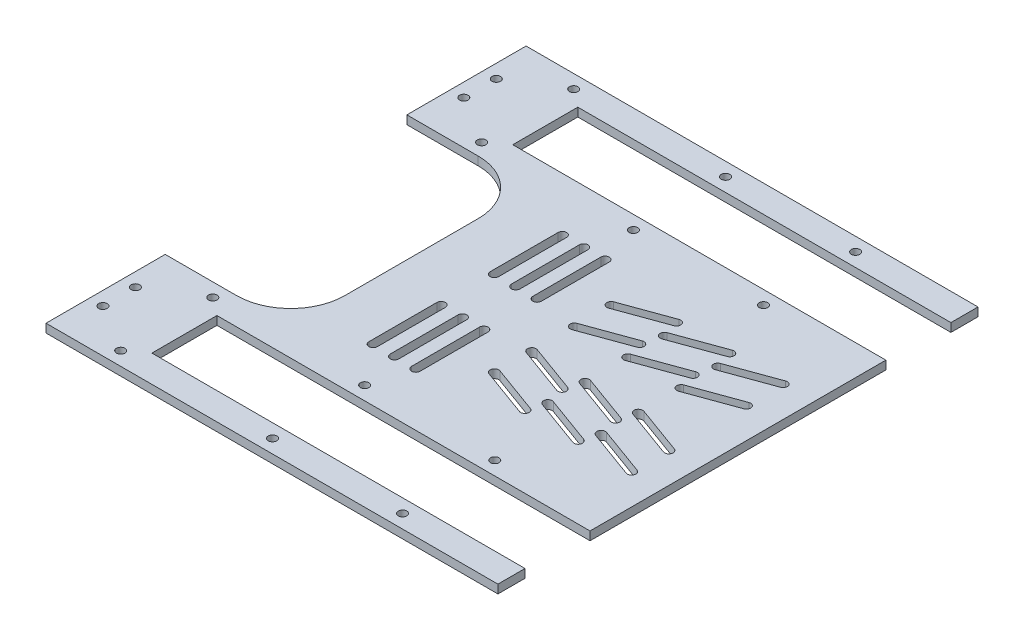
SolidWorks part; units mm, degrees
ref_plane "Front Plane" through (0, 0, 0) normal (0, 0, 1) x (1, 0, 0)
ref_plane "Top Plane" through (0, 0, 0) normal (0, 1, 0) x (1, 0, 0)
ref_plane "Right Plane" through (0, 0, 0) normal (1, 0, 0) x (0, 0, -1)
sketch "Sketch1" plane through (0, 0, 0) normal (0, 1, 0) x (1, 0, 0)
  line L0 (-55.952, 28.5339) -> (-55.9511, 28.5339)
  line L1 (-55.9511, 28.5339) -> (-55.9511, 28.321)
  line L2 (-55.9511, 28.321) -> (-21.4553, 28.321)
  line L3 (-21.4553, 28.321) -> (-21.4553, -28.321)
  line L4 (-21.4553, -28.321) -> (-55.952, -28.321)
  line L5 (-55.952, -28.321) -> (-55.952, -63.881)
  line L6 (-55.952, -63.881) -> (55.046, -63.881)
  line L7 (55.046, -63.881) -> (55.046, -57.531)
  line L8 (55.046, -57.531) -> (32.4585, -57.531)
  line L10 (32.4585, -34.671) -> (55.046, -34.671)
  line L11 (55.046, -34.671) -> (55.046, 34.671)
  line L12 (55.046, 34.671) -> (32.4585, 34.671)
  line L14 (32.4585, 57.531) -> (55.046, 57.531)
  line L15 (55.046, 57.531) -> (55.046, 63.881)
  line L16 (55.046, 63.881) -> (-55.952, 63.881)
  line L17 (-55.952, 63.881) -> (-55.952, 28.5339)
  line L18 (-21.4553, 0) -> (55.046, 0) construction
  line L19 (-55.952, -46.101) -> (-28.5899, -46.101) construction
  line L20 (32.4585, -34.671) -> (-28.5899, -34.671)
  line L21 (-28.5899, -34.671) -> (-28.5899, -46.101)
  line L22 (-28.5899, -46.101) -> (-28.5899, -57.531)
  line L23 (-28.5899, -57.531) -> (32.4585, -57.531)
  line L24 (-28.5899, 57.531) -> (32.4585, 57.531)
  line L25 (-28.5899, 46.101) -> (-28.5899, 57.531)
  line L26 (-28.5899, 34.671) -> (-28.5899, 46.101)
  line L27 (32.4585, 34.671) -> (-28.5899, 34.671)
  dimension "D1" = 28.321
  dimension "D2" = 27.3621
extrude "Boss-Extrude1" add sketch "Sketch1" along normal blind 2
fillet "Fillet1" radius 12.7 2 edges at (-21.4553, 1, 28.321) (-21.4553, 1, -28.321)
sketch "Sketch2" plane through (0, 2, 0) normal (0, 1, 0) x (1, 0, 0)
  line L36 (0, 0) -> (55.046, 0) construction
  line L37 (55.046, -34.671) -> (55.046, 34.671) construction
  circle A0 centre (51.871, 0) radius 1
  circle A1 centre (51.871, 14.1605) radius 1
  circle A2 centre (-18.2803, 0) radius 1
  circle A3 centre (-18.2803, -14.1605) radius 1
  circle A4 centre (-18.2803, 14.1605) radius 1
  circle A5 centre (-36.539, 31.496) radius 1
  circle A6 centre (-0.9481, 31.496) radius 1
  circle A7 centre (29.5319, 31.4883) radius 1
  circle A8 centre (-52.777, 45.1485) radius 1
  circle A9 centre (-52.777, 53.4035) radius 1
  circle A10 centre (-36.539, 60.706) radius 1
  circle A11 centre (-0.9481, 60.706) radius 1
  circle A12 centre (29.5319, 60.7137) radius 1
  circle A13 centre (29.5319, -60.7137) radius 1
  circle A14 centre (-0.9481, -60.706) radius 1
  circle A15 centre (-36.539, -60.706) radius 1
  circle A16 centre (-52.777, -53.4035) radius 1
  circle A17 centre (-52.777, -45.1485) radius 1
  circle A18 centre (29.5319, -31.4883) radius 1
  circle A19 centre (-0.9481, -31.496) radius 1
  circle A20 centre (-36.539, -31.496) radius 1
  circle A21 centre (51.871, -14.1605) radius 1
  dimension "D1" = 2
extrude "Cut-Extrude1" cut sketch "Sketch2" against normal through all both and the other way through all
sketch "Sketch3" plane through (0, 2, 0) normal (0, 1, 0) x (1, 0, 0)
  line L0 (-28.5899, -57.531) -> (-32.3999, -57.531)
  line L1 (-32.3999, -57.531) -> (-32.3999, -34.671)
  line L2 (-32.3999, -34.671) -> (-28.5899, -34.671)
  line L3 (-28.5899, -34.671) -> (-28.5899, -57.531)
  line L4 (-21.4553, 0) -> (55.046, 0) construction
  line L5 (-21.4553, 15.621) -> (-21.4553, -15.621) construction
  line L6 (55.046, -34.671) -> (55.046, 34.671) construction
  line L7 (-28.5899, 34.671) -> (-28.5899, 57.531)
  line L8 (-32.3999, 34.671) -> (-28.5899, 34.671)
  line L9 (-32.3999, 57.531) -> (-32.3999, 34.671)
  line L10 (-28.5899, 57.531) -> (-32.3999, 57.531)
  dimension "D1" = 3.81
extrude "Cut-Extrude2" cut sketch "Sketch3" against normal through all both and the other way through all
sketch "Sketch5" plane through (0, 2, 0) normal (0, 1, 0) x (1, 0, 0)
  line L0 (-18.2803, 0) -> (-8.2803, 0) construction
  line L1 (-8.2803, -34.671) -> (-8.2803, 34.671) construction
  line L2 (55.046, 34.671) -> (-32.3999, 34.671) construction
  line L3 (-8.2803, 34.671) -> (-8.2803, 22.171) construction
  line L4 (-8.2803, -34.671) -> (-8.2803, -22.171) construction
  line L5 (-8.2803, -6.25) -> (-8.2803, 6.25) construction
  line L6 (-8.2803, 22.171) -> (-8.2803, 6.25) construction
  line L7 (-7.2803, 22.171) -> (-7.2803, 6.25)
  line L8 (-9.2803, 22.171) -> (-9.2803, 6.25)
  line L9 (-8.2803, -22.171) -> (-8.2803, -6.25) construction
  line L10 (-7.2803, -22.171) -> (-7.2803, -6.25)
  line L11 (-9.2803, -22.171) -> (-9.2803, -6.25)
  line L12 (-7.2803, 14.2105) -> (-4.2803, 14.2105) construction
  line L13 (-5.7803, 14.2105) -> (-5.7803, 6.25) construction
  line L14 (-3.2803, 22.171) -> (-3.2803, 6.25) construction
  line L15 (-4.2803, 22.171) -> (-4.2803, 6.25)
  line L16 (-2.2803, 22.171) -> (-2.2803, 6.25)
  line L17 (-2.2803, 14.2105) -> (0.7197, 14.2105) construction
  line L18 (-0.7803, 14.2105) -> (-0.7803, 6.25) construction
  line L19 (1.7197, 22.171) -> (1.7197, 6.25) construction
  line L20 (2.7197, 22.171) -> (2.7197, 6.25)
  line L21 (0.7197, 22.171) -> (0.7197, 6.25)
  line L22 (1.7197, -22.171) -> (1.7197, -6.25) construction
  line L23 (2.7197, -22.171) -> (2.7197, -6.25)
  line L24 (0.7197, -22.171) -> (0.7197, -6.25)
  line L25 (-3.2803, -22.171) -> (-3.2803, -6.25) construction
  line L26 (-4.2803, -22.171) -> (-4.2803, -6.25)
  line L27 (-2.2803, -22.171) -> (-2.2803, -6.25)
  arc A0 (-7.2803, 22.171) -> (-9.2803, 22.171) centre (-8.2803, 22.171) ccw
  arc A1 (-9.2803, 6.25) -> (-7.2803, 6.25) centre (-8.2803, 6.25) ccw
  arc A2 (-7.2803, -22.171) -> (-9.2803, -22.171) centre (-8.2803, -22.171) cw
  arc A3 (-9.2803, -6.25) -> (-7.2803, -6.25) centre (-8.2803, -6.25) cw
  arc A4 (-4.2803, 22.171) -> (-2.2803, 22.171) centre (-3.2803, 22.171) cw
  arc A5 (-2.2803, 6.25) -> (-4.2803, 6.25) centre (-3.2803, 6.25) cw
  arc A6 (2.7197, 22.171) -> (0.7197, 22.171) centre (1.7197, 22.171) ccw
  arc A7 (0.7197, 6.25) -> (2.7197, 6.25) centre (1.7197, 6.25) ccw
  arc A8 (2.7197, -22.171) -> (0.7197, -22.171) centre (1.7197, -22.171) cw
  arc A9 (0.7197, -6.25) -> (2.7197, -6.25) centre (1.7197, -6.25) cw
  arc A10 (-4.2803, -22.171) -> (-2.2803, -22.171) centre (-3.2803, -22.171) ccw
  arc A11 (-2.2803, -6.25) -> (-4.2803, -6.25) centre (-3.2803, -6.25) ccw
  point P8 (-8.2803, 0)
  point P13 (-8.2803, 0)
  point P14 (-8.2803, 14.2105)
  point P19 (-8.2803, -14.2105)
  point P30 (-3.2803, 14.2105)
  point P41 (1.7197, 14.2105)
  point P48 (1.7197, -14.2105)
  point P55 (-3.2803, -14.2105)
  dimension "D1" = 10
  dimension "D2" = 3
  dimension "D3" = 12.5
  dimension "D4" = 12.5
  dimension "D5" = 2
  dimension "D6" = 3
extrude "Cut-Extrude3" cut sketch "Sketch5" against normal through all
sketch "Sketch6" plane through (0, 2, 0) normal (0, 1, 0) x (1, 0, 0)
  line L0 (2.7197, 14.2105) -> (8.7197, 14.2105) construction
  line L1 (2.7197, 6.25) -> (2.7197, 22.171) construction
  line L2 (0, 0) -> (8.7197, 0) construction
  line L3 (8.7197, -5) -> (8.7197, 5)
  line L4 (8.7197, 5) -> (11.7197, 5) construction
  line L5 (11.7197, 5) -> (26.6806, 10.4453) construction
  line L6 (-9.2803, 22.171) -> (-9.2803, 6.25) construction
  line L7 (19.2001, 7.7227) -> (26.6806, 10.4453) construction
  line L10 (22.9403, 9.084) -> (11.7197, 5)
  line L11 (22.9403, 9.084) -> (11.7197, 5) construction
  line L12 (23.2824, 8.1443) -> (12.0617, 4.0603)
  line L13 (22.5983, 10.0237) -> (11.3777, 5.9397)
  line L14 (35.4403, 9.084) -> (24.2197, 5) construction
  line L15 (35.7824, 8.1443) -> (24.5617, 4.0603)
  line L16 (35.0983, 10.0237) -> (23.8777, 5.9397)
  line L17 (47.9403, 9.084) -> (36.7197, 5) construction
  line L18 (48.2824, 8.1443) -> (37.0617, 4.0603)
  line L19 (47.5983, 10.0237) -> (36.3777, 5.9397)
  line L20 (22.9403, 9.084) -> (35.4403, 9.084) construction
  line L21 (17.33, 7.042) -> (17.33, 15.542) construction
  line L22 (22.8709, 17.7515) -> (11.6503, 13.6675) construction
  line L23 (23.2129, 16.8118) -> (11.9923, 12.7279)
  line L24 (22.5289, 18.6912) -> (11.3083, 14.6072)
  line L25 (35.3709, 17.7515) -> (24.1503, 13.6675) construction
  line L26 (35.7129, 16.8118) -> (24.4923, 12.7279)
  line L27 (35.0289, 18.6912) -> (23.8083, 14.6072)
  line L28 (47.8709, 17.7515) -> (36.6503, 13.6675) construction
  line L29 (48.2129, 16.8118) -> (36.9923, 12.7279)
  line L30 (47.5289, 18.6912) -> (36.3083, 14.6072)
  line L31 (22.8709, 17.7515) -> (35.3709, 17.7515) construction
  line L32 (8.7197, 0) -> (51.871, 0) construction
  line L33 (47.9403, -9.084) -> (36.7197, -5) construction
  line L34 (48.2824, -8.1443) -> (37.0617, -4.0603)
  line L35 (47.5983, -10.0237) -> (36.3777, -5.9397)
  line L36 (35.4403, -9.084) -> (24.2197, -5) construction
  line L37 (35.7824, -8.1443) -> (24.5617, -4.0603)
  line L38 (35.0983, -10.0237) -> (23.8777, -5.9397)
  line L39 (22.9403, -9.084) -> (11.7197, -5) construction
  line L40 (23.2824, -8.1443) -> (12.0617, -4.0603)
  line L41 (22.5983, -10.0237) -> (11.3777, -5.9397)
  line L42 (47.8709, -17.7515) -> (36.6503, -13.6675) construction
  line L43 (48.2129, -16.8118) -> (36.9923, -12.7279)
  line L44 (47.5289, -18.6912) -> (36.3083, -14.6072)
  line L45 (35.3709, -17.7515) -> (24.1503, -13.6675) construction
  line L46 (35.7129, -16.8118) -> (24.4923, -12.7279)
  line L47 (35.0289, -18.6912) -> (23.8083, -14.6072)
  line L48 (22.8709, -17.7515) -> (11.6503, -13.6675) construction
  line L49 (23.2129, -16.8118) -> (11.9923, -12.7279)
  line L50 (22.5289, -18.6912) -> (11.3083, -14.6072)
  arc A0 (23.2824, 8.1443) -> (22.5983, 10.0237) centre (22.9403, 9.084) ccw
  arc A1 (11.3777, 5.9397) -> (12.0617, 4.0603) centre (11.7197, 5) ccw
  arc A2 (35.7824, 8.1443) -> (35.0983, 10.0237) centre (35.4403, 9.084) ccw
  arc A3 (23.8777, 5.9397) -> (24.5617, 4.0603) centre (24.2197, 5) ccw
  arc A4 (48.2824, 8.1443) -> (47.5983, 10.0237) centre (47.9403, 9.084) ccw
  arc A5 (36.3777, 5.9397) -> (37.0617, 4.0603) centre (36.7197, 5) ccw
  arc A6 (23.2129, 16.8118) -> (22.5289, 18.6912) centre (22.8709, 17.7515) ccw
  arc A7 (11.3083, 14.6072) -> (11.9923, 12.7279) centre (11.6503, 13.6675) ccw
  arc A8 (35.7129, 16.8118) -> (35.0289, 18.6912) centre (35.3709, 17.7515) ccw
  arc A9 (23.8083, 14.6072) -> (24.4923, 12.7279) centre (24.1503, 13.6675) ccw
  arc A10 (48.2129, 16.8118) -> (47.5289, 18.6912) centre (47.8709, 17.7515) ccw
  arc A11 (36.3083, 14.6072) -> (36.9923, 12.7279) centre (36.6503, 13.6675) ccw
  arc A12 (48.2824, -8.1443) -> (47.5983, -10.0237) centre (47.9403, -9.084) cw
  arc A13 (36.3777, -5.9397) -> (37.0617, -4.0603) centre (36.7197, -5) cw
  arc A14 (35.7824, -8.1443) -> (35.0983, -10.0237) centre (35.4403, -9.084) cw
  arc A15 (23.8777, -5.9397) -> (24.5617, -4.0603) centre (24.2197, -5) cw
  arc A16 (23.2824, -8.1443) -> (22.5983, -10.0237) centre (22.9403, -9.084) cw
  arc A17 (11.3777, -5.9397) -> (12.0617, -4.0603) centre (11.7197, -5) cw
  arc A18 (48.2129, -16.8118) -> (47.5289, -18.6912) centre (47.8709, -17.7515) cw
  arc A19 (36.3083, -14.6072) -> (36.9923, -12.7279) centre (36.6503, -13.6675) cw
  arc A20 (35.7129, -16.8118) -> (35.0289, -18.6912) centre (35.3709, -17.7515) cw
  arc A21 (23.8083, -14.6072) -> (24.4923, -12.7279) centre (24.1503, -13.6675) cw
  arc A22 (23.2129, -16.8118) -> (22.5289, -18.6912) centre (22.8709, -17.7515) cw
  arc A23 (11.3083, -14.6072) -> (11.9923, -12.7279) centre (11.6503, -13.6675) cw
  point P9 (8.7197, 0)
  point P18 (17.33, 7.042)
  point P26 (29.83, 7.042)
  point P33 (42.33, 7.042)
  point P44 (29.7606, 15.7095)
  point P47 (17.2606, 15.7095)
  point P59 (42.2606, 15.7095)
  point P68 (42.33, -7.042)
  point P75 (29.83, -7.042)
  point P82 (17.33, -7.042)
  point P89 (42.2606, -15.7095)
  point P96 (29.7606, -15.7095)
  point P103 (17.2606, -15.7095)
  dimension "D6" = 160
  dimension "D1" = 6
  dimension "D2" = 10
  dimension "D3" = 3
  dimension "D4" = 2
  dimension "D5" = 8.7197
  dimension "D7" = 3
  dimension "D8" = 12.5
  dimension "D9" = 8.5
  dimension "D10" = 3
  dimension "D11" = 12.5
  dimension "D12" = 11.9407
  dimension "D13" = 13.6675
  dimension "D14" = 11.6503
extrude "Cut-Extrude4" cut sketch "Sketch6" against normal through all contours L23 A7 L24 A6 | L26 A9 L27 A8 | L29 A11 L30 A10 | L18 A5 L19 A4 | L15 A3 L16 A2 | L12 A1 L13 A0 | L38 A15 L37 A14 | L41 A17 L40 A16 | L35 A13 L34 A12 | L43 A19 L44 A18 | L46 A21 L47 A20 | L49 A23 L50 A22
sketch "Sketch7" plane through (0, 0, 0) normal (0, -1, 0) x (1, 0, 0)
  line L0 (-57.9178, 63.881) -> (-55.952, 63.881)
  line L1 (-55.952, 63.881) -> (-55.952, 28.321)
  line L2 (-55.952, 28.321) -> (-57.9178, 28.321)
  line L3 (-57.9178, 28.321) -> (-57.9178, 63.881)
  line L4 (-21.4553, 0) -> (55.046, 0) construction
  line L5 (-21.4553, -15.621) -> (-21.4553, 15.621) construction
  line L6 (55.046, 34.671) -> (55.046, -34.671) construction
  line L7 (-57.9178, -28.321) -> (-57.9178, -63.881)
  line L8 (-55.952, -28.321) -> (-57.9178, -28.321)
  line L9 (-55.952, -63.881) -> (-55.952, -28.321)
  line L10 (-57.9178, -63.881) -> (-55.952, -63.881)
  circle A0 centre (-54.7428, 53.4035) radius 1
  circle A1 centre (-54.7428, 45.1485) radius 1
  circle A2 centre (-54.7428, -45.1485) radius 1
  circle A3 centre (-54.7428, -53.4035) radius 1
extrude "Cut-Extrude5" cut sketch "Sketch7" against normal through all
sketch "Sketch9" plane through (0, 0, 0) normal (0, -1, 0) x (1, 0, 0)
  line L0 (-52.777, 53.4035) -> (-47.697, 53.4035) construction
  line L1 (-52.777, 45.1485) -> (-47.697, 45.1485) construction
  line L2 (-55.952, 63.881) -> (-50.872, 63.881)
  line L3 (-55.952, 63.881) -> (55.046, 63.881) construction
  line L4 (-50.872, 63.881) -> (-50.872, 28.321)
  line L5 (-34.1553, 28.321) -> (-55.952, 28.321) construction
  line L6 (-50.872, 28.321) -> (-55.952, 28.321)
  line L7 (-55.952, 28.321) -> (-55.952, 63.881)
  line L8 (-21.4553, 0) -> (55.046, 0) construction
  line L9 (-21.4553, -15.621) -> (-21.4553, 15.621) construction
  line L10 (55.046, 34.671) -> (55.046, -34.671) construction
  line L11 (-52.777, -45.1485) -> (-47.697, -45.1485) construction
  line L12 (-52.777, -53.4035) -> (-47.697, -53.4035) construction
  line L13 (-55.952, -28.321) -> (-55.952, -63.881)
  line L14 (-50.872, -28.321) -> (-55.952, -28.321)
  line L15 (-50.872, -63.881) -> (-50.872, -28.321)
  line L16 (-55.952, -63.881) -> (-50.872, -63.881)
  circle A0 centre (-47.697, 53.4035) radius 1
  circle A1 centre (-47.697, 45.1485) radius 1
  arc A2 (-53.7599, 53.2194) -> (-53.7599, 53.5876) centre (-52.777, 53.4035) ccw construction
  circle A3 centre (-47.697, -45.1485) radius 1
  circle A4 centre (-47.697, -53.4035) radius 1
  dimension "D1" = 5.08
  dimension "D2" = 5.08
  dimension "D3" = 5.08
extrude "Cut-Extrude6" cut sketch "Sketch9" against normal through all
sketch "Sketch10" plane through (0, 2, 0) normal (0, 1, 0) x (1, 0, 0)
  line L1 (-16.6494, -19.9028) -> (-19.9112, -19.9028)
  line L2 (-16.6494, -19.9028) -> (-16.6494, 19.9028)
  line L3 (-16.6494, 19.9028) -> (-19.9112, 19.9028)
  line L4 (-19.9112, -19.9028) -> (-19.9112, 19.9028)
  line L5 (-16.6494, -19.9028) -> (-19.9112, 19.9028) construction
  line L6 (-16.6494, 19.9028) -> (-19.9112, -19.9028) construction
  line L7 (53.619, -18.7932) -> (50.123, -18.7932)
  line L8 (53.619, -18.7932) -> (53.619, 18.7932)
  line L9 (53.619, 18.7932) -> (50.123, 18.7932)
  line L10 (50.123, -18.7932) -> (50.123, 18.7932)
  line L11 (53.619, -18.7932) -> (50.123, 18.7932) construction
  line L12 (53.619, 18.7932) -> (50.123, -18.7932) construction
  point P0 (-18.2803, 0)
  point P6 (51.871, 0)
extrude "Boss-Extrude2" add sketch "Sketch10" against normal up to surface (2 mm away) up to face at (-47.697, 0, 44.1485)
sketch "Sketch11" plane through (0, 2, 0) normal (0, 1, 0) x (1, 0, 0)
  line L0 (-32.3999, -34.671) -> (-32.3999, -42.291) construction
  line L1 (-32.3999, -34.671) -> (-32.3999, -57.531) construction
  line L2 (-32.3999, -42.291) -> (-50.872, -42.291)
  line L3 (-50.872, -28.321) -> (-50.872, -63.881) construction
  line L4 (-50.872, -42.291) -> (-50.872, -34.671)
  line L5 (-50.872, -34.671) -> (-32.3999, -34.671)
  line L6 (-32.3999, -34.671) -> (-32.3999, -42.291)
  dimension "D1" = 7.62
extrude "Cut-Extrude7" cut sketch "Sketch11" against normal through all
sketch "Sketch12" plane through (0, 2, 0) normal (0, 1, 0) x (1, 0, 0)
  line L0 (-32.3999, 34.671) -> (-69.841, 34.671)
  line L1 (-69.841, 34.671) -> (-69.841, 70.714)
  line L2 (-69.841, 70.714) -> (61.6729, 70.714)
  line L3 (61.6729, 70.714) -> (61.6729, 34.671)
  line L4 (61.6729, 34.671) -> (-32.3999, 34.671)
  dimension "D1" = 36.043
  dimension "D2" = 131.5138
  dimension "D3" = 69.841
extrude "Cut-Extrude8" cut sketch "Sketch12" against normal through all
sketch "Sketch13" plane through (0, 2, 0) normal (0, 1, 0) x (1, 0, 0)
  line L3 (55.046, 49.911) -> (-32.3999, 49.911)
  line L4 (55.046, 56.261) -> (55.046, 49.911)
  line L5 (-50.872, 56.261) -> (55.046, 56.261)
  line L18 (-32.3999, 34.671) -> (-50.872, 34.671)
  line L19 (-50.872, 56.261) -> (-50.872, 34.671)
  line L20 (-32.3999, 34.671) -> (-32.3999, 49.911)
  circle A0 centre (29.5319, 53.0937) radius 1
  circle A16 centre (-0.9481, 53.086) radius 1
  circle A17 centre (-36.539, 53.086) radius 1
  circle A18 centre (-47.697, 45.7835) radius 1
  circle A19 centre (-47.697, 37.5285) radius 1
extrude "Boss-Extrude3" add sketch "Sketch13" against normal up to surface (2 mm away) up to face at (42.2606, 0, 15.7095)
sketch "Sketch14" plane through (0, 2, 0) normal (0, 1, 0) x (1, 0, 0)
  line L6 (-32.3999, -42.291) -> (-50.872, -42.291)
  line L7 (-50.872, -42.291) -> (-50.872, -63.881)
  line L8 (-50.872, -63.881) -> (55.046, -63.881)
  line L9 (55.046, -63.881) -> (55.046, -57.531)
  line L10 (55.046, -57.531) -> (-32.3999, -57.531)
  line L11 (-32.3999, -57.531) -> (-32.3999, -42.291)
  line L12 (-32.3999, -42.291) -> (-50.872, -42.291)
  line L13 (-50.872, -42.291) -> (-50.872, -63.881)
  line L14 (-50.872, -63.881) -> (55.046, -63.881)
  line L15 (55.046, -63.881) -> (55.046, -57.531)
  line L16 (55.046, -57.531) -> (-32.3999, -57.531)
  line L17 (-32.3999, -57.531) -> (-32.3999, -42.291)
  dimension "D1" = 0
extrude "Cut-Extrude9" cut sketch "Sketch14" against normal through all
sketch "Sketch15" plane through (0, 2, 0) normal (0, 1, 0) x (1, 0, 0)
  line L0 (-21.4553, 0) -> (55.046, 0) construction
  line L1 (-21.4553, 15.621) -> (-21.4553, -15.621) construction
  line L2 (55.046, -34.671) -> (55.046, 34.671) construction
  line L3 (55.046, 56.261) -> (-50.872, 56.261) construction
  line L4 (55.046, 49.911) -> (55.046, 56.261) construction
  line L5 (-32.3999, 34.671) -> (-32.3999, 49.911) construction
  line L6 (-32.3999, 49.911) -> (55.046, 49.911) construction
  line L7 (55.046, 56.261) -> (-50.872, 56.261) construction
  line L8 (55.046, 49.911) -> (55.046, 56.261) construction
  line L9 (-32.3999, 34.671) -> (-32.3999, 49.911) construction
  line L10 (-32.3999, 49.911) -> (55.046, 49.911) construction
  line L11 (-32.3999, 34.671) -> (-50.872, 34.671) construction
  line L12 (-50.872, 56.261) -> (-50.872, 28.321) construction
  line L13 (-50.872, 34.671) -> (-50.872, 56.261) construction
  line L14 (-50.872, -34.671) -> (-50.872, -56.261)
  line L15 (-32.3999, -34.671) -> (-50.872, -34.671)
  line L16 (-32.3999, -49.911) -> (55.046, -49.911)
  line L17 (-32.3999, -34.671) -> (-32.3999, -49.911)
  line L18 (55.046, -49.911) -> (55.046, -56.261)
  line L19 (55.046, -56.261) -> (-50.872, -56.261)
  circle A0 centre (29.5319, 53.0937) radius 1 construction
  circle A1 centre (-0.9481, 53.086) radius 1 construction
  circle A2 centre (-36.539, 53.086) radius 1 construction
  circle A3 centre (-47.697, 37.5285) radius 1 construction
  circle A4 centre (-47.697, 45.7835) radius 1 construction
  circle A5 centre (29.5319, 53.0937) radius 1 construction
  circle A6 centre (-0.9481, 53.086) radius 1 construction
  circle A7 centre (-36.539, 53.086) radius 1 construction
  circle A8 centre (-47.697, 37.5285) radius 1 construction
  circle A9 centre (-47.697, 45.7835) radius 1 construction
  circle A10 centre (-47.697, -45.7835) radius 1
  circle A11 centre (-47.697, -37.5285) radius 1
  circle A12 centre (-36.539, -53.086) radius 1
  circle A13 centre (-0.9481, -53.086) radius 1
  circle A14 centre (29.5319, -53.0937) radius 1
extrude "Boss-Extrude6" add sketch "Sketch15" against normal up to surface (2 mm away) up to face at (42.2606, 0, 15.7095)
sketch "Sketch16" plane through (0, 0, 0) normal (0, -1, 0) x (1, 0, 0)
  line L1 (-50.3879, -51.1853) -> (-45.8759, -51.1853)
  line L2 (-50.3879, -51.1853) -> (-50.3879, -33.0367)
  line L3 (-50.3879, -33.0367) -> (-45.8759, -33.0367)
  line L4 (-45.8759, -51.1853) -> (-45.8759, -33.0367)
  line L5 (-50.3879, -51.1853) -> (-45.8759, -33.0367) construction
  line L6 (-50.3879, -33.0367) -> (-45.8759, -51.1853) construction
  line L7 (-50.2413, 35.4433) -> (-43.9893, 35.4433)
  line L8 (-50.2413, 35.4433) -> (-50.2413, 48.5156)
  line L9 (-50.2413, 48.5156) -> (-43.9893, 48.5156)
  line L10 (-43.9893, 35.4433) -> (-43.9893, 48.5156)
  line L11 (-50.2413, 35.4433) -> (-43.9893, 48.5156) construction
  line L12 (-50.2413, 48.5156) -> (-43.9893, 35.4433) construction
  point P0 (-48.1319, -42.111)
  point P5 (-47.1153, 41.9794)
extrude "Boss-Extrude7" add sketch "Sketch16" against normal up to surface (2 mm away) up to face at (-6.0429, 2, 0)
sketch "Sketch17" plane through (0, 2, 0) normal (0, 1, 0) x (1, 0, 0)
  line L0 (-50.872, -38.481) -> (-47.697, -38.481) construction
  line L1 (-32.3999, -42.291) -> (-50.872, -42.291) construction
  line L2 (-21.4553, 0) -> (55.046, 0) construction
  line L3 (-21.4553, 15.621) -> (-21.4553, -15.621) construction
  line L4 (-50.872, -28.321) -> (-50.872, -56.261) construction
  line L5 (-32.3999, -34.671) -> (-32.3999, -49.911) construction
  line L6 (-32.3999, -42.291) -> (-32.3999, -34.671) construction
  line L7 (-32.3999, -38.481) -> (-54.8352, -38.481) construction
  line L8 (55.046, -34.671) -> (55.046, 34.671) construction
  circle A0 centre (-47.697, -38.481) radius 1
  circle A1 centre (-36.539, -31.496) radius 1 construction
  circle A2 centre (-47.697, -46.101) radius 1
  circle A3 centre (-47.697, 38.481) radius 1
  circle A4 centre (-47.697, 46.101) radius 1
  dimension "D2" = 3.175
extrude "Cut-Extrude10" cut sketch "Sketch17" against normal through all
